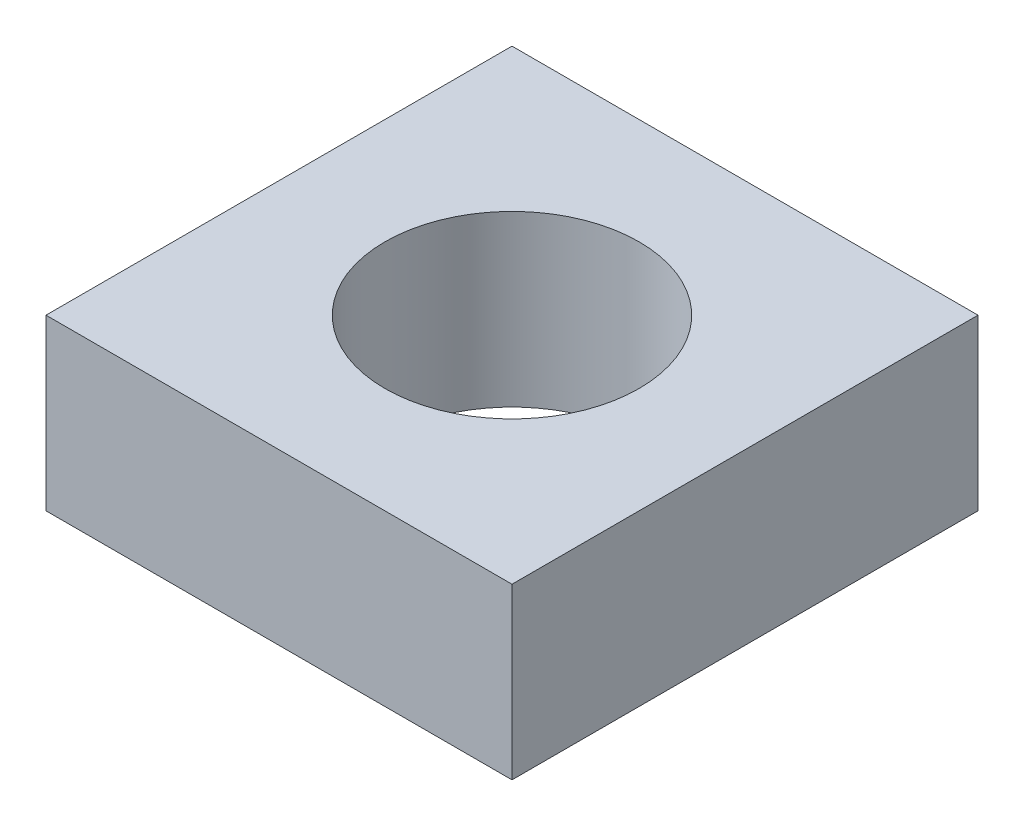
SolidWorks part; units mm, degrees
ref_plane "前视基准面" through (0, 0, 0) normal (0, 0, 1) x (1, 0, 0)
ref_plane "上视基准面" through (0, 0, 0) normal (0, 1, 0) x (1, 0, 0)
ref_plane "右视基准面" through (0, 0, 0) normal (1, 0, 0) x (0, 0, -1)
sketch "草图1" plane through (0, 0, 0) normal (0, 1, 0) x (1, 0, 0)
  line L1 (-2.75, 2.75) -> (2.75, 2.75)
  line L2 (-2.75, 2.75) -> (-2.75, -2.75)
  line L3 (-2.75, -2.75) -> (2.75, -2.75)
  line L4 (2.75, 2.75) -> (2.75, -2.75)
  line L5 (-2.75, 2.75) -> (2.75, -2.75) construction
  line L6 (-2.75, -2.75) -> (2.75, 2.75) construction
  circle A0 centre (0, 0) radius 1.5
  point P0 (0, 0)
  dimension "D2" = 3
  dimension "D1" = 5.5
extrude "凸台-拉伸1" add sketch "草图1" along normal blind 2
